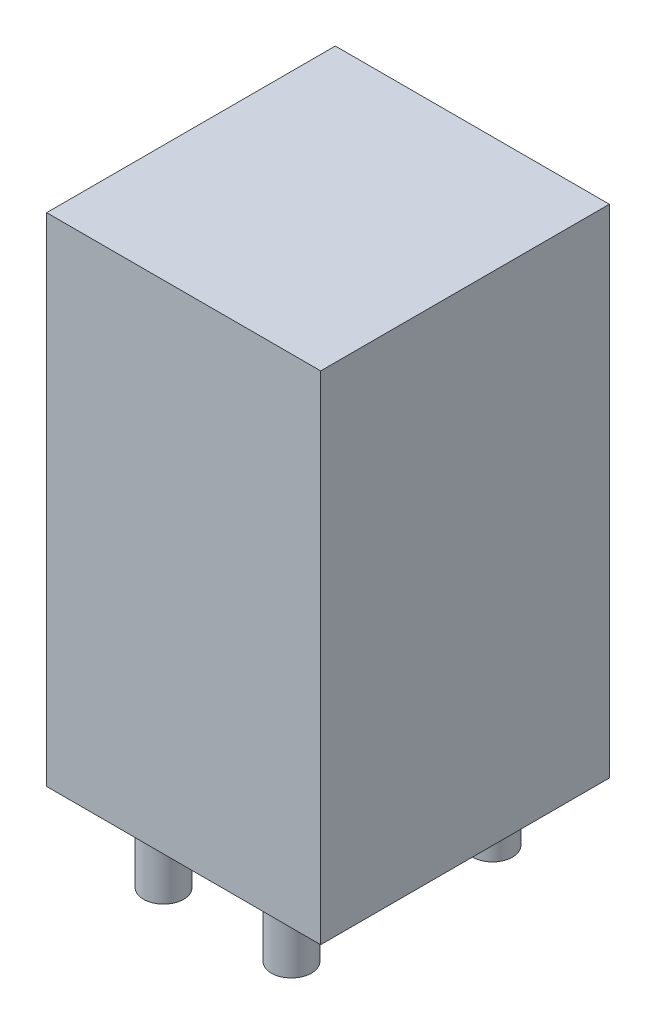
SolidWorks part; units mm, degrees
ref_plane "Front Plane" through (0, 0, 0) normal (0, 0, 1) x (1, 0, 0)
ref_plane "Top Plane" through (0, 0, 0) normal (0, 1, 0) x (1, 0, 0)
ref_plane "Right Plane" through (0, 0, 0) normal (1, 0, 0) x (0, 0, -1)
sketch "Sketch1" plane through (0, 0, 0) normal (0, 1, 0) x (1, 0, 0)
  line L1 (0, 0) -> (7.5, 0)
  line L2 (0, 0) -> (0, 7.9)
  line L3 (0, 7.9) -> (7.5, 7.9)
  line L4 (7.5, 0) -> (7.5, 7.9)
  dimension "D1" = 7.5
  dimension "D2" = 7.9
extrude "Boss-Extrude1" add sketch "Sketch1" along normal blind 13.6
sketch "Sketch2" plane through (0, 0, 0) normal (0, -1, 0) x (-1, 0, 0)
  line L0 (0, 3.95) -> (-7.5, 3.95) construction
  line L1 (0, 7.9) -> (0, 0) construction
  line L2 (-7.5, 0) -> (-7.5, 7.9) construction
  line L3 (-3.75, 0) -> (-3.75, 7.9) construction
  line L4 (0, 0) -> (-7.5, 0) construction
  line L5 (-7.5, 7.9) -> (0, 7.9) construction
  line L6 (-2, 0) -> (-2, 7.9) construction
  circle A0 centre (-2, 1.2) radius 0.55
  circle A1 centre (-2, 6.7) radius 0.55
  circle A2 centre (-5.5, 1.2) radius 0.55
  circle A3 centre (-5.5, 6.7) radius 0.55
  point P22 (0, 0)
  point P23 (0, 0)
  point P24 (0, 0)
  dimension "D2" = 1.1
  dimension "D3" = 5.5
  dimension "D5" = 3.5
  dimension "D1" = 2
  dimension "D4" = 2.75
extrude "Boss-Extrude2" add sketch "Sketch2" along normal blind 2
